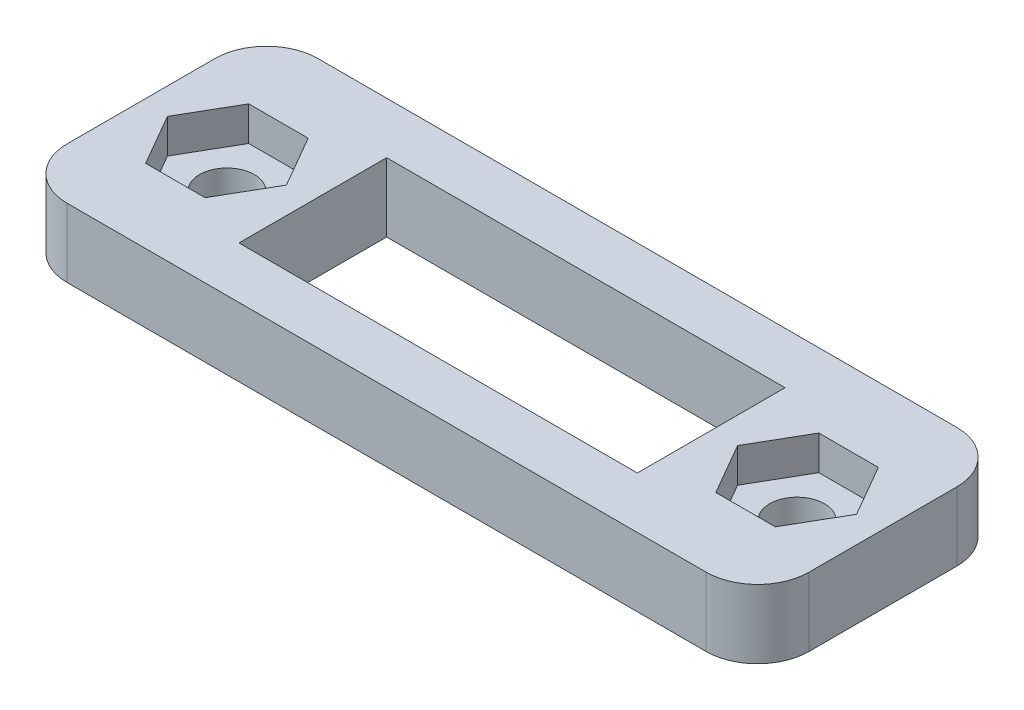
SolidWorks part; units mm, degrees
ref_plane "Front Plane" through (0, 0, 0) normal (0, 0, 1) x (1, 0, 0)
ref_plane "Top Plane" through (0, 0, 0) normal (0, 1, 0) x (1, 0, 0)
ref_plane "Right Plane" through (0, 0, 0) normal (1, 0, 0) x (0, 0, -1)
sketch "Sketch1" plane through (0, 0, 0) normal (0, 1, 0) x (1, 0, 0)
  line L1 (-11.6, 4.3) -> (11.6, 4.3)
  line L2 (-11.6, 4.3) -> (-11.6, -4.3)
  line L3 (-11.6, -4.3) -> (11.6, -4.3)
  line L4 (11.6, 4.3) -> (11.6, -4.3)
  line L9 (-21.6, 7.3) -> (21.6, 7.3)
  line L10 (-21.6, 7.3) -> (-21.6, -7.3)
  line L11 (-21.6, -7.3) -> (21.6, -7.3)
  line L12 (21.6, 7.3) -> (21.6, -7.3)
  point P4 (0, 4.3)
  point P6 (-11.6, 0)
  point P11 (0, 7.3)
  point P12 (-21.6, 0)
  dimension "D1" = 23.2
  dimension "D2" = 8.6
  dimension "D3" = 3
  dimension "D4" = 10
extrude "Boss-Extrude1" add sketch "Sketch1" along normal blind 4
sketch "Sketch4" plane through (0, 4, 0) normal (0, 1, 0) x (1, 0, 0)
  line L0 (21.6, -7.3) -> (21.6, 7.3) construction
  line L1 (18.3321, -3) -> (20.0641, 0)
  line L2 (20.0641, 0) -> (18.3321, 3)
  line L3 (18.3321, 3) -> (14.8679, 3)
  line L4 (14.8679, 3) -> (13.1359, 0)
  line L5 (13.1359, 0) -> (14.8679, -3)
  line L6 (14.8679, -3) -> (18.3321, -3)
  line L7 (0, 7.3) -> (0, -7.3) construction
  line L8 (21.6, 7.3) -> (-21.6, 7.3) construction
  line L9 (-21.6, -7.3) -> (21.6, -7.3) construction
  line L10 (-14.8679, -3) -> (-18.3321, -3)
  line L11 (-13.1359, 0) -> (-14.8679, -3)
  line L12 (-14.8679, 3) -> (-13.1359, 0)
  line L13 (-18.3321, 3) -> (-14.8679, 3)
  line L14 (-20.0641, 0) -> (-18.3321, 3)
  line L15 (-18.3321, -3) -> (-20.0641, 0)
  circle A0 centre (16.6, 0) radius 3 construction
  dimension "D1" = 5
  dimension "D2" = 6
extrude "Cut-Extrude1" cut sketch "Sketch4" against normal blind 2
sketch "Sketch5" plane through (0, 2, 0) normal (0, 1, 0) x (1, 0, 0)
  line L0 (0, 4.3) -> (0, -4.3) construction
  line L1 (11.6, 4.3) -> (-11.6, 4.3) construction
  line L2 (-11.6, -4.3) -> (11.6, -4.3) construction
  line L3 (-21.6, 7.3) -> (-21.6, -7.3) construction
  circle A0 centre (-16.6, 0) radius 1.6
  circle A1 centre (16.6, 0) radius 1.6
  dimension "D1" = 3.2
  dimension "D2" = 5
extrude "Cut-Extrude2" cut sketch "Sketch5" against normal through all
fillet "Fillet2" radius 3 4 edges at (21.6, 2, -7.3) (-21.6, 2, -7.3) (-21.6, 2, 7.3) (21.6, 2, 7.3)
